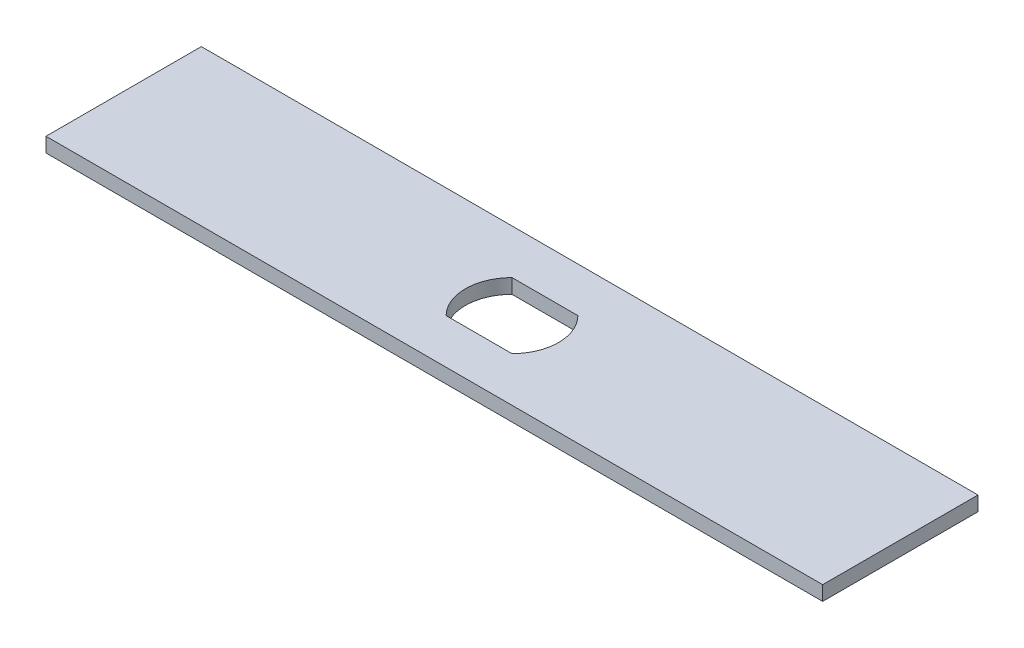
SolidWorks part; units mm, degrees
ref_plane "Front Plane" through (0, 0, 0) normal (0, 0, 1) x (1, 0, 0)
ref_plane "Top Plane" through (0, 0, 0) normal (0, 1, 0) x (1, 0, 0)
ref_plane "Right Plane" through (0, 0, 0) normal (1, 0, 0) x (0, 0, -1)
sketch "Sketch1" plane through (0, 0, 0) normal (0, 1, 0) x (1, 0, 0)
  line L1 (0, 0) -> (254, 0)
  line L2 (0, 0) -> (0, -50.8)
  line L3 (0, -50.8) -> (254, -50.8)
  line L4 (254, 0) -> (254, -50.8)
  line L5 (116.2237, -14.6237) -> (137.7763, -14.6237)
  line L6 (137.7763, -36.1763) -> (116.2237, -36.1763)
  circle A0 centre (127, -25.4) radius 15.24
  arc A1 (111.76, -25.4) -> (116.2237, -14.6237) centre (127, -25.4) cw
  arc A2 (142.24, -25.4) -> (137.7763, -14.6237) centre (127, -25.4) ccw
  arc A3 (111.76, -25.4) -> (114.5161, -34.1413) centre (127, -25.4) cw
  arc A4 (142.24, -25.4) -> (137.7763, -36.1763) centre (127, -25.4) cw
  dimension "D1" = 254
  dimension "D2" = 50.8
extrude "Boss-Extrude1" add sketch "Sketch1" along normal blind 4.7498 contours L4 L1 L2 L3 A0 | L5 A0 | L6 A0
